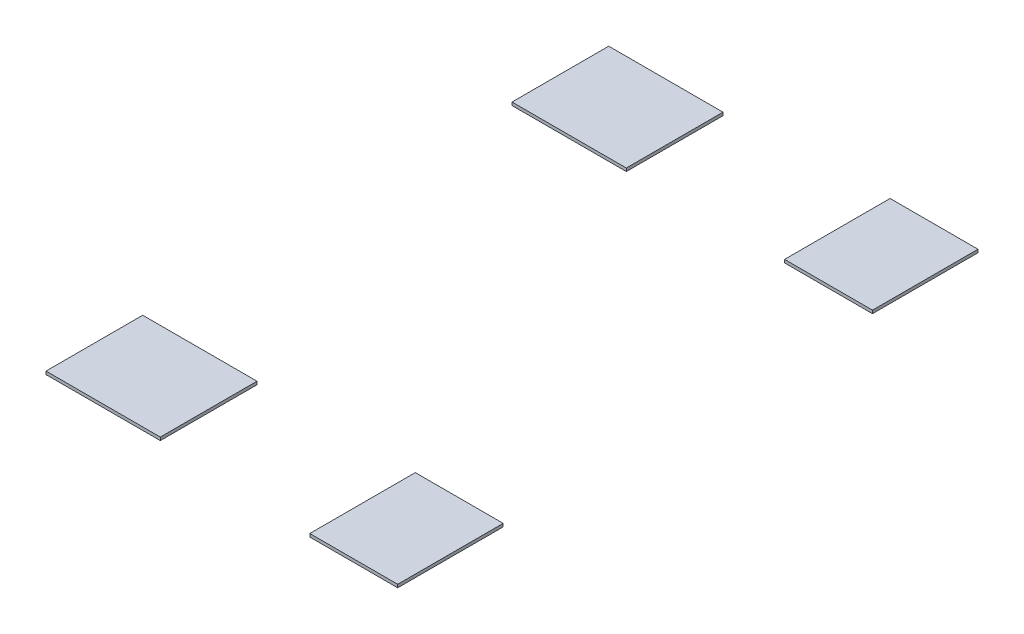
SolidWorks part; units mm, degrees
material "Copper"
ref_plane "Front Plane" through (0, 0, 0) normal (0, 0, 1) x (1, 0, 0)
ref_plane "Top Plane" through (0, 0, 0) normal (0, 1, 0) x (1, 0, 0)
ref_plane "Right Plane" through (0, 0, 0) normal (1, 0, 0) x (0, 0, -1)
sketch "Sketch2" plane through (0, 0, 0) normal (0, 1, 0) x (1, 0, 0)
  line L0 (0, 0) -> (0, 4.0537) construction
  line L1 (0, 0) -> (3.4695, 0) construction
  line L2 (-1.675, 0.45) -> (-1.325, 0.45) construction
  line L3 (-1.675, -0.45) -> (-1.325, -0.45) construction
  line L4 (-1.5, 0.45) -> (-1.5, -0.45) construction
  line L5 (0, 0) -> (-3.0313, 0) construction
  line L6 (1.45, 3.3) -> (2.45, 3.3)
  line L7 (1.45, 3.3) -> (1.45, 2.1)
  line L8 (1.45, 2.1) -> (2.45, 2.1)
  line L9 (2.45, 3.3) -> (2.45, 2.1)
  line L10 (-0.35, 2.1) -> (-1.65, 2.1)
  line L11 (-0.35, 2.1) -> (-0.35, 3.2)
  line L12 (-0.35, 3.2) -> (-1.65, 3.2)
  line L13 (-1.65, 2.1) -> (-1.65, 3.2)
  line L14 (2.45, -3.3) -> (2.45, -2.1)
  line L15 (1.45, -2.1) -> (2.45, -2.1)
  line L16 (1.45, -3.3) -> (2.45, -3.3)
  line L17 (1.45, -3.3) -> (1.45, -2.1)
  line L18 (-0.35, -2.1) -> (-1.65, -2.1)
  line L19 (-0.35, -2.1) -> (-0.35, -3.2)
  line L20 (-0.35, -3.2) -> (-1.65, -3.2)
  line L21 (-1.65, -2.1) -> (-1.65, -3.2)
  circle A0 centre (1.5, 0) radius 0.45 construction
  arc A1 (-1.675, 0.45) -> (-1.675, -0.45) centre (-1.675, 0) ccw construction
  arc A2 (-1.325, -0.45) -> (-1.325, 0.45) centre (-1.325, 0) ccw construction
  dimension "D1" = 0.9
  dimension "D2" = 0.9
  dimension "D3" = 1.25
  dimension "D4" = 3
  dimension "D5" = 1.2
  dimension "D6" = 1.65
  dimension "D7" = 1.1
  dimension "D8" = 1
  dimension "D9" = 0.35
  dimension "D10" = 4.1
  dimension "D11" = 2.1
  dimension "D12" = 2.1
  dimension "D13" = 1.5
extrude "Boss-Extrude1" add sketch "Sketch2" along normal blind 0.035
